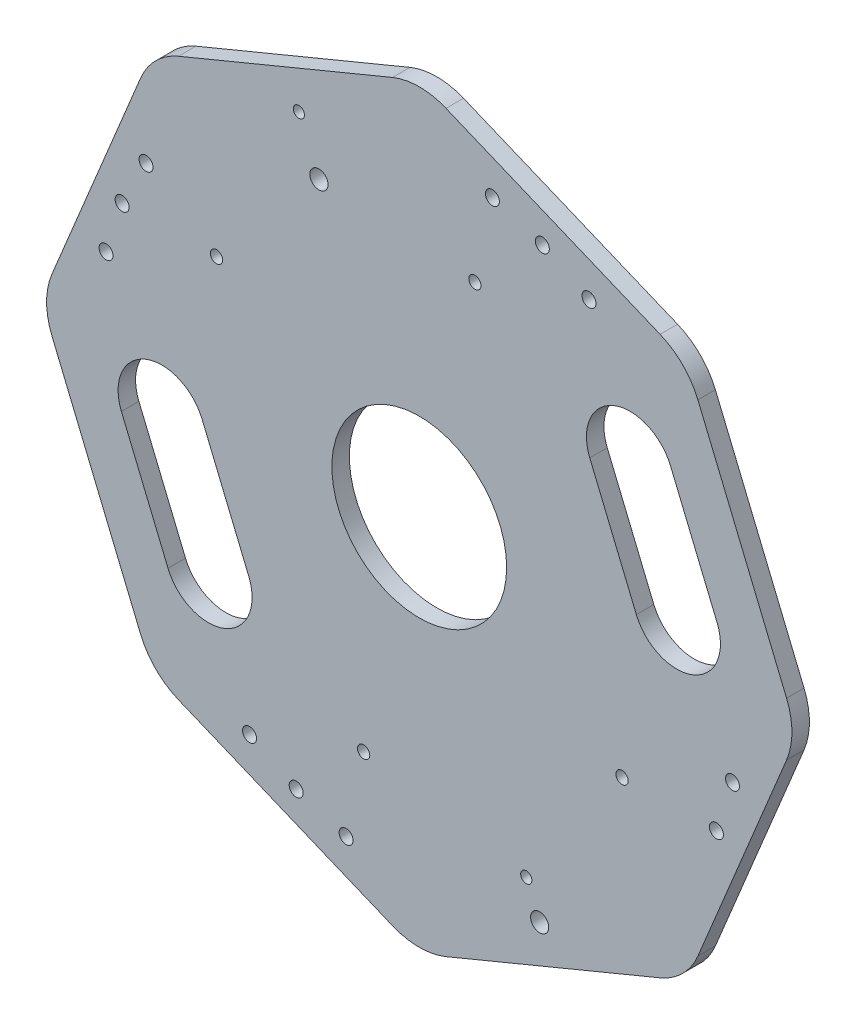
SolidWorks part; units mm, degrees
ref_plane "前视基准面" through (0, 0, 0) normal (0, 0, 1) x (1, 0, 0)
ref_plane "上视基准面" through (0, 0, 0) normal (0, 1, 0) x (1, 0, 0)
ref_plane "右视基准面" through (0, 0, 0) normal (1, 0, 0) x (0, 0, -1)
sketch "草图1" plane through (0, 0, 0) normal (0, 0, 1) x (1, 0, 0)
  line L0 (0, 121.5223) -> (0, -117.9323) construction
  line L1 (-126.6637, 0) -> (129.3981, 0) construction
  line L2 (0, 108.2392) -> (-76.5367, 76.5367)
  line L3 (-76.5367, 76.5367) -> (-108.2392, 0)
  line L4 (-108.2392, 0) -> (-76.5367, -76.5367)
  line L5 (-76.5367, -76.5367) -> (0, -108.2392)
  line L6 (0, -108.2392) -> (76.5367, -76.5367)
  line L7 (76.5367, -76.5367) -> (108.2392, 0)
  line L8 (108.2392, 0) -> (76.5367, 76.5367)
  line L9 (76.5367, 76.5367) -> (0, 108.2392)
  line L10 (-17.4834, -36.185) -> (0.9849, -80.7715) construction
  line L11 (-17.4834, -36.185) -> (58.7828, -4.5945) construction
  line L12 (0.9849, -80.7715) -> (77.2511, -49.181) construction
  line L13 (58.7828, -4.5945) -> (77.2511, -49.181) construction
  line L14 (-38.2683, -92.388) -> (38.2683, 92.388) construction
  line L15 (-92.388, 38.2683) -> (92.388, -38.2683) construction
  line L16 (-58.0028, 35.506) -> (-15.9076, -66.1207) construction
  line L17 (-58.0028, 35.506) -> (15.9076, 66.1207) construction
  line L18 (-15.9076, -66.1207) -> (58.0028, -35.506) construction
  line L19 (15.9076, 66.1207) -> (58.0028, -35.506) construction
  line L20 (-38.2683, 92.388) -> (0, 0) construction
  line L25 (-92.388, -38.2683) -> (0, 0) construction
  line L30 (-73.6462, -11.654) -> (-60.3163, -43.8351) construction
  line L31 (-62.0977, -6.8704) -> (-48.7678, -39.0516)
  line L32 (-85.1947, -16.4375) -> (-71.8648, -48.6187)
  line L33 (60.3163, 43.8351) -> (73.6462, 11.654) construction
  line L34 (48.7678, 39.0516) -> (62.0977, 6.8704)
  line L35 (71.8648, 48.6187) -> (85.1947, 16.4375)
  line L36 (0, 0) -> (38.2683, -92.388) construction
  circle A0 centre (0, 0) radius 100 construction
  circle A5 centre (-35.2069, -84.9969) radius 2
  circle A6 centre (84.9969, -35.2069) radius 2
  circle A7 centre (35.2069, 84.9969) radius 2
  circle A8 centre (-84.9969, 35.2069) radius 2
  circle A12 centre (-58.0028, 35.506) radius 1.75
  circle A13 centre (-15.9076, -66.1207) radius 1.75
  circle A14 centre (58.0028, -35.506) radius 1.75
  circle A15 centre (15.9076, 66.1207) radius 1.75
  circle A25 centre (0, 0) radius 92 construction
  circle A27 centre (89.5883, -20.9269) radius 2
  circle A28 centre (-20.9269, -89.5883) radius 2
  circle A29 centre (-89.5883, 20.9269) radius 2
  circle A30 centre (20.9269, 89.5883) radius 2
  circle A39 centre (-48.551, -78.146) radius 2
  circle A40 centre (-78.146, 48.551) radius 2
  circle A41 centre (48.551, 78.146) radius 2
  circle A43 centre (78.146, -48.551) radius 2 [skipped]
  circle A44 centre (0, 0) radius 25
  arc A45 (-62.0977, -6.8704) -> (-85.1947, -16.4375) centre (-73.6462, -11.654) ccw
  arc A46 (-71.8648, -48.6187) -> (-48.7678, -39.0516) centre (-60.3163, -43.8351) ccw
  arc A47 (48.7678, 39.0516) -> (71.8648, 48.6187) centre (60.3163, 43.8351) cw
  arc A48 (85.1947, 16.4375) -> (62.0977, 6.8704) centre (73.6462, 11.654) cw
  circle A49 centre (-34.4415, 83.1492) radius 1.6
  circle A50 centre (-28.7013, 69.291) radius 2.6
  circle A53 centre (30.6147, -73.9104) radius 1.6
  circle A54 centre (34.4415, -83.1492) radius 2.6
  point P22 (-66.9813, -27.7445)
  point P52 (66.9813, 27.7445)
  point P76 (0, 0)
  point P85 (0, 0)
  dimension "D6" = 50
  dimension "D7" = 25
  dimension "D8" = 15
  dimension "D9" = 3.2
  dimension "D10" = 4
  dimension "D11" = 4
  dimension "D12" = 4
  dimension "D13" = 4
  dimension "D14" = 8
  dimension "D15" = 8
  dimension "D16" = 8
  dimension "D17" = 8
  dimension "D20" = 25
  dimension "D25" = 3.5
  dimension "D26" = 3.5
  dimension "D27" = 3.5
  dimension "D28" = 3.5
  dimension "D29" = 5.2
  dimension "D30" = 3.2
  dimension "D31" = 10
  dimension "D32" = 20
  dimension "D37" = 92
  dimension "D38" = 15
  dimension "D39" = 4
  dimension "D33" = 92
  dimension "D34" = 15
  dimension "D35" = 4
  dimension "D18" = 5.2
  dimension "D1" = 200
  dimension "D2" = 48.26
  dimension "D3" = 82.55
  dimension "D4" = 70
  dimension "D5" = 25
  dimension "D19" = 10
  dimension "D21" = 110
  dimension "D22" = 80
  dimension "D23" = 45
  dimension "D24" = 40
  dimension "D36" = 4
  dimension "D40" = 4
extrude "凸台-拉伸1" add sketch "草图1" along normal blind 5
fillet "圆角1" radius 20 8 edges at (-76.5367, 76.5367, 2.5) (0, 108.2392, 2.5) (76.5367, 76.5367, 2.5) (108.2392, 0, 2.5) (76.5367, -76.5367, 2.5) (0, -108.2392, 2.5) (-76.5367, -76.5367, 2.5) (-108.2392, 0, 2.5)
